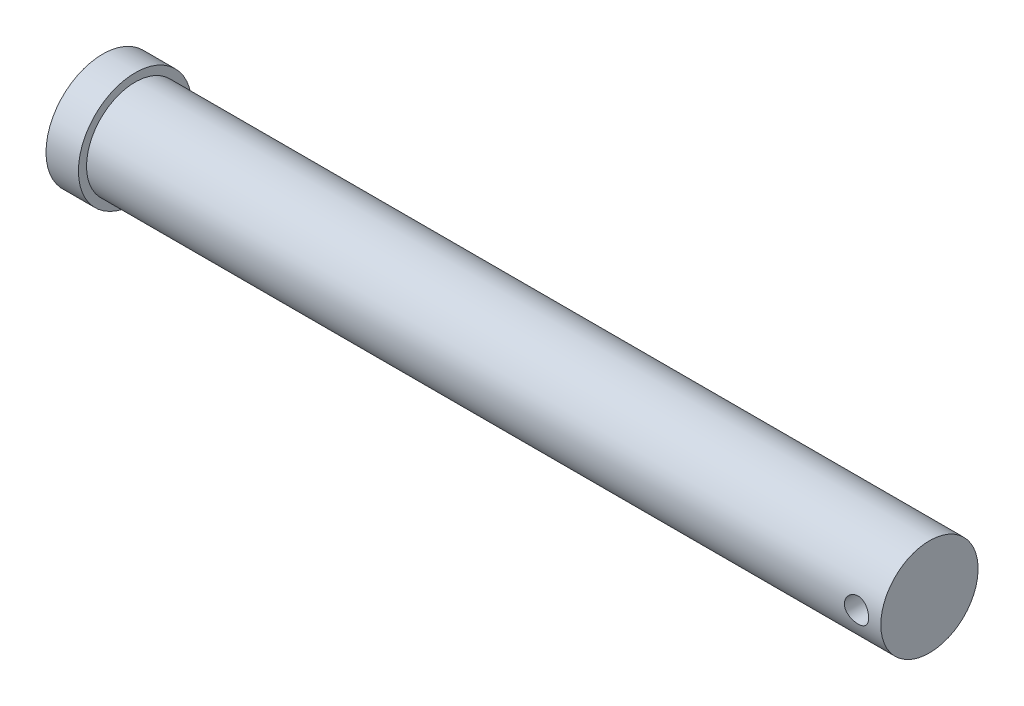
SolidWorks part; units mm, degrees
ref_plane "Ön Düzlem" through (0, 0, 0) normal (0, 0, 1) x (1, 0, 0)
ref_plane "Üst Düzlem" through (0, 0, 0) normal (0, 1, 0) x (1, 0, 0)
ref_plane "Sağ Düzlem" through (0, 0, 0) normal (1, 0, 0) x (0, 0, -1)
sketch "Çizim1" plane through (0, 0, 0) normal (0, 0, 1) x (1, 0, 0)
  line L0 (0, 0) -> (510, 0) construction
  line L1 (0, 0) -> (0, 35)
  line L2 (0, 35) -> (20, 35)
  line L3 (20, 35) -> (20, 30)
  line L4 (20, 30) -> (510, 30)
  line L5 (510, 30) -> (510, 0)
  line L6 (0, 0) -> (510, 0)
  dimension "D1" = 510
  dimension "D2" = 20
  dimension "D3" = 5
  dimension "D4" = 30
revolve "Döndür1" add sketch "Çizim1" angle 360 about L0
sketch "Çizim2" plane through (0, 0, 0) normal (0, 0, 1) x (1, 0, 0)
  line L0 (510, -30) -> (510, 30) construction
  circle A0 centre (495, 0) radius 7.5
  dimension "D2" = 15
  dimension "D1" = 15
extrude "Kes-Ekstrüzyon1" cut sketch "Çizim2" against normal mid plane 60
